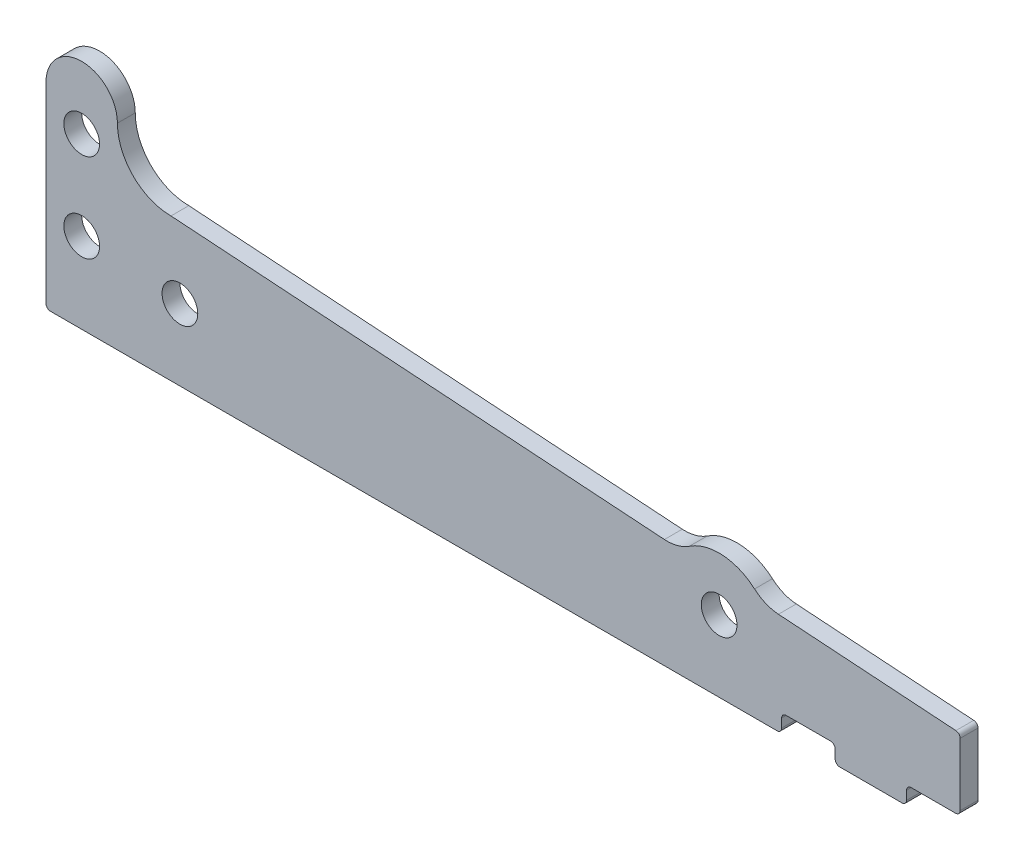
SolidWorks part; units mm, degrees
ref_plane "Front Plane" through (0, 0, 0) normal (0, 0, 1) x (1, 0, 0)
ref_plane "Top Plane" through (0, 0, 0) normal (0, 1, 0) x (1, 0, 0)
ref_plane "Right Plane" through (0, 0, 0) normal (1, 0, 0) x (0, 0, -1)
sketch "Sketch1" plane through (0, 0, 0) normal (0, 0, 1) x (1, 0, 0)
  line L0 (3.175, 19.05) -> (3.175, 0) construction
  line L1 (0, 0) -> (6.35, 0) construction
  line L2 (0, 0) -> (0, 19.05)
  line L3 (0, 19.05) -> (6.35, 19.05)
  line L4 (6.35, 0) -> (6.35, 19.05) construction
  line L5 (3.175, 13.462) -> (3.175, 5.588) construction
  line L6 (6.35, 0) -> (81.2824, 0) construction
  line L9 (0, 0) -> (0, -1.5875)
  line L10 (0, -1.5875) -> (81.2824, -1.5875)
  line L11 (81.2824, -1.5875) -> (81.2824, 0)
  line L12 (0, 19.05) -> (-1.5875, 19.05) construction
  line L13 (-1.5875, 19.05) -> (-1.5875, -1.5875) construction
  line L14 (-1.5875, -1.5875) -> (0, -1.5875) construction
  line L15 (81.2824, 11.1125) -> (6.35, 11.1125) construction
  line L16 (81.2824, 0) -> (81.2824, 11.1125) construction
  line L17 (11.1125, 11.1125) -> (81.2824, 6.35)
  line L18 (81.2824, 6.35) -> (81.2824, 0)
  line L19 (11.9062, -1.5875) -> (11.9062, 4.7625) construction
  line L20 (59.8512, -1.5875) -> (59.8512, 4.7625) construction
  line L21 (81.2824, -1.5875) -> (76.5199, -1.5875)
  line L22 (81.2824, -1.5875) -> (81.2824, 0)
  line L23 (81.2824, 0) -> (76.5199, 0)
  line L24 (76.5199, -1.5875) -> (76.5199, 0)
  line L25 (81.2824, -1.5875) -> (76.5199, 0) construction
  line L26 (81.2824, 0) -> (76.5199, -1.5875) construction
  line L27 (70.1699, 0) -> (65.4074, 0)
  line L28 (70.1699, 0) -> (70.1699, -1.5875)
  line L29 (70.1699, -1.5875) -> (65.4074, -1.5875)
  line L30 (65.4074, 0) -> (65.4074, -1.5875)
  line L31 (70.1699, 0) -> (65.4074, -1.5875) construction
  line L32 (70.1699, -1.5875) -> (65.4074, 0) construction
  circle A0 centre (3.175, 13.462) radius 1.5875
  circle A1 centre (3.175, 5.588) radius 1.5875
  circle A2 centre (3.175, 15.875) radius 3.175
  circle A3 centre (3.175, 3.175) radius 3.175
  circle A4 centre (11.1125, 15.875) radius 4.7625
  circle A5 centre (11.9062, 4.7625) radius 1.5875
  circle A6 centre (59.8512, 4.7625) radius 1.5875
  circle A7 centre (59.8512, 4.7625) radius 4.7625
  point P11 (3.175, 9.525)
  point P12 (3.175, 9.525)
  point P30 (6.35, 15.875)
  point P44 (78.9012, -0.7937)
  point P49 (67.7887, -0.7938)
  dimension "D1" = 19.05
  dimension "D2" = 3.175
  dimension "D8" = 11.1125
  dimension "D9" = 6.35
  dimension "D10" = 15.875
  dimension "D14" = 5.5562
  dimension "D3" = 6.35
  dimension "D4" = 7.874
  dimension "D5" = 1.5875
  dimension "D6" = 82.8699
  dimension "D7" = 1.5875
  dimension "D11" = 6.35
  dimension "D12" = 5.5563
  dimension "D13" = 6.35
extrude "Boss-Extrude1" add sketch "Sketch1" along normal blind 1.5875
fillet "Fillet1" radius 0.4064 9 edges at (81.2824, 6.35, 0.7937) (81.2824, 0, 0.7937) (76.5199, 0, 0.7937) (76.5199, -1.5875, 0.7937) (70.1699, -1.5875, 0.7937) (70.1699, 0, 0.7937) (65.4074, 0, 0.7937) (65.4074, -1.5875, 0.7937) (0, -1.5875, 0.7937)
fillet "Fillet2" radius 3.5719 2 edges at (56.395, 8.0391, 0.7937) (63.7184, 7.5421, 0.7937)
